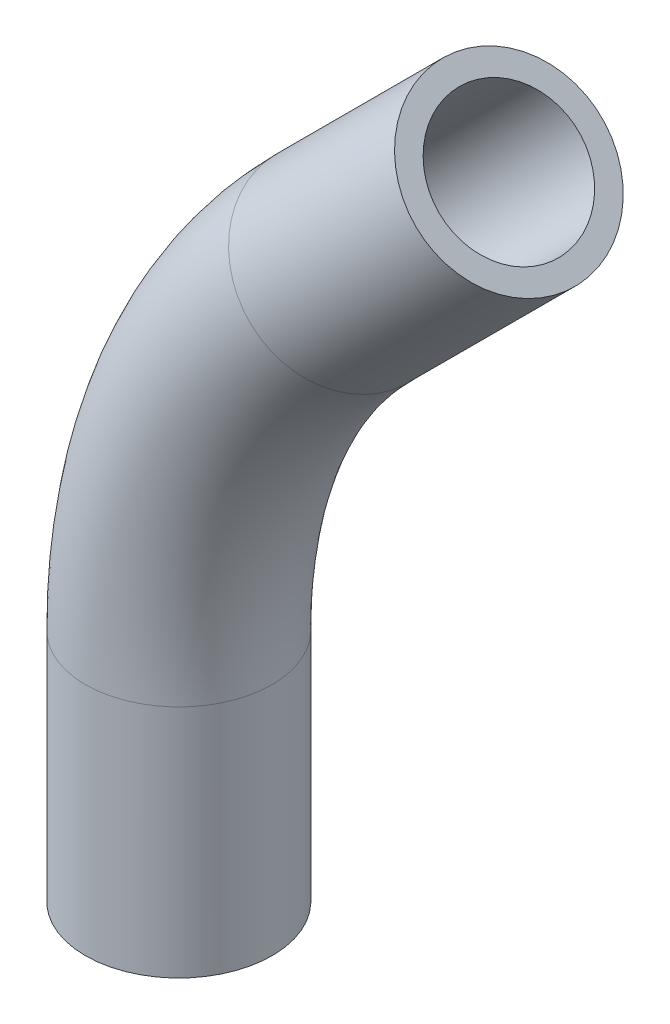
SolidWorks part; units mm, degrees
ref_plane "Front Plane" through (0, 0, 0) normal (0, 0, 1) x (1, 0, 0)
ref_plane "Top Plane" through (0, 0, 0) normal (0, 1, 0) x (1, 0, 0)
ref_plane "Right Plane" through (0, 0, 0) normal (1, 0, 0) x (0, 0, -1)
sketch "Sketch1" plane through (0, 0, 0) normal (0, 0, 1) x (1, 0, 0)
  line L0 (0, 0) -> (0, 10.0589)
  line L1 (7.0294, 27.0294) -> (14.1421, 34.1421)
  arc A0 (0, 10.0589) -> (7.0294, 27.0294) centre (24, 10.0589) cw
  point P6 (0, 20)
  dimension "D3" = 24
  dimension "D1" = 20
  dimension "D2" = 20
  dimension "D4" = 135
sketch "Sketch2" plane through (0, 0, 0) normal (0, 1, 0) x (1, 0, 0)
  circle A0 centre (0, 0) radius 4
  circle A1 centre (0, 0) radius 3
  dimension "D1" = 6
  dimension "D2" = 8
sweep "Sweep1" add profiles "Sketch2" path "Sketch1"
